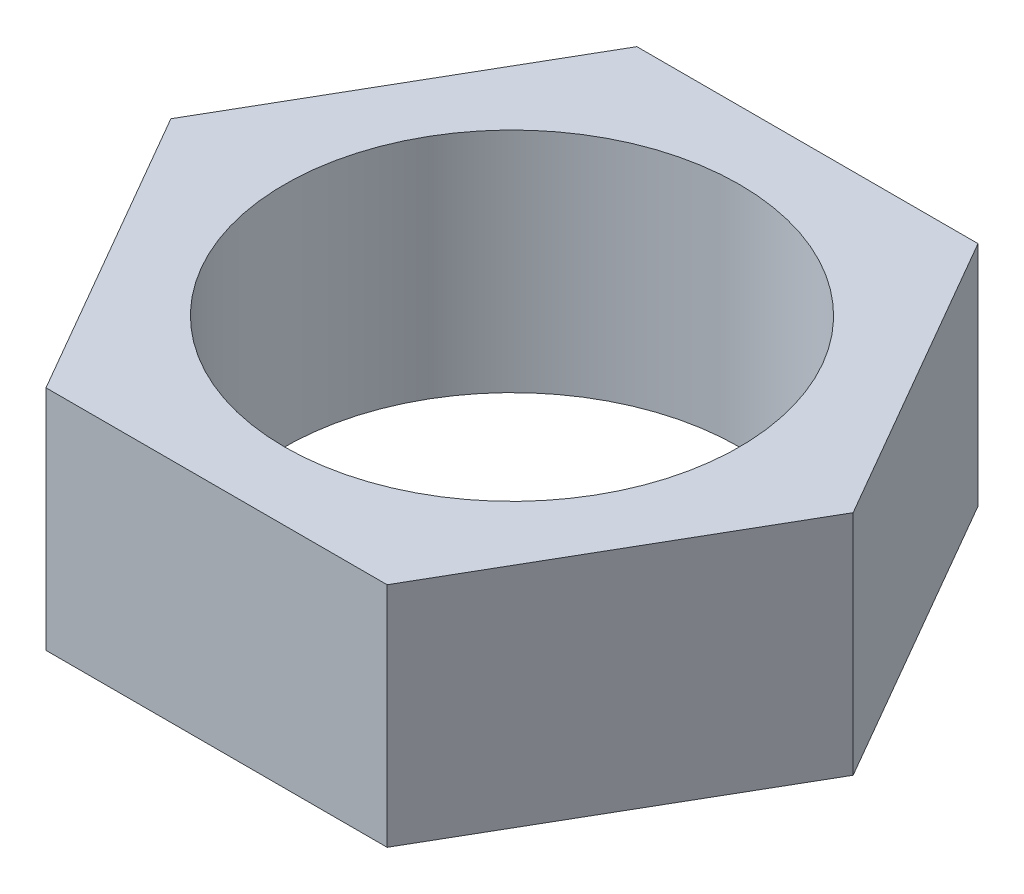
SolidWorks part; units mm, degrees
material "1060 合金"
ref_plane "前视基准面" through (0, 0, 0) normal (0, 0, 1) x (1, 0, 0)
ref_plane "上视基准面" through (0, 0, 0) normal (0, 1, 0) x (1, 0, 0)
ref_plane "右视基准面" through (0, 0, 0) normal (1, 0, 0) x (0, 0, -1)
other "Configuration Table"
sketch "草图1" plane through (0, 0, 0) normal (0, 1, 0) x (1, 0, 0)
  line L1 (1.5, 2.5981) -> (-1.5, 2.5981)
  line L2 (-1.5, 2.5981) -> (-3, 0)
  line L3 (-3, 0) -> (-1.5, -2.5981)
  line L4 (-1.5, -2.5981) -> (1.5, -2.5981)
  line L5 (1.5, -2.5981) -> (3, 0)
  line L6 (3, 0) -> (1.5, 2.5981)
  circle A0 centre (0, 0) radius 2.5981 construction
  circle A1 centre (0, 0) radius 2
  dimension "D1" = 4
  dimension "D2" = 3
extrude "凸台-拉伸1" add sketch "草图1" along normal blind 2
